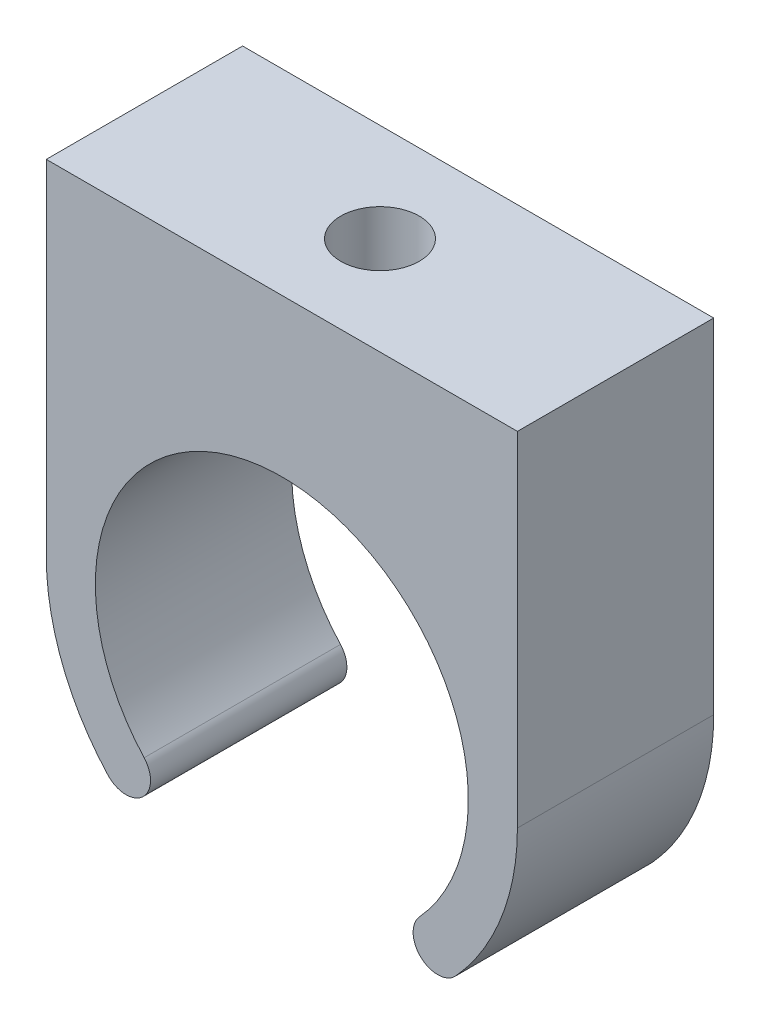
SolidWorks part; units mm, degrees
ref_plane "Front Plane" through (0, 0, 0) normal (0, 0, 1) x (1, 0, 0)
ref_plane "Top Plane" through (0, 0, 0) normal (0, 1, 0) x (1, 0, 0)
ref_plane "Right Plane" through (0, 0, 0) normal (1, 0, 0) x (0, 0, -1)
sketch "Sketch3" plane through (0, 0, 0) normal (0, 0, 1) x (1, 0, 0)
  line L2 (-12, -4.5) -> (-12, 13)
  line L3 (-12, 13) -> (12, 13)
  line L4 (12, -4.5) -> (12, 13)
  line L5 (-10.1145, -10.9573) -> (3.8592, 4.1808) construction
  line L6 (-5.6289, 6.0979) -> (10.1145, -10.9573) construction
  arc A1 (7.0143, -10.907) -> (-7.0143, -10.907) centre (0, -4.5) ccw
  arc A2 (8.8602, -12.593) -> (12, -4.5) centre (0, -4.5) ccw
  arc A3 (-8.8602, -12.593) -> (-7.0143, -10.907) centre (-7.9373, -11.75) ccw
  arc A4 (7.0143, -10.907) -> (8.8602, -12.593) centre (7.9373, -11.75) ccw
  arc A5 (-12, -4.5) -> (-8.8602, -12.593) centre (0, -4.5) ccw
  point P0 (0, 0)
  dimension "D4" = 19
  dimension "D2" = 12
  dimension "D1" = 24
extrude "Boss-Extrude2" add sketch "Sketch3" along normal mid plane 10
sketch "Sketch5" plane through (0, 13, 0) normal (0, 1, 0) x (1, 0, 0)
  line L0 (-12, 5) -> (12, -5) construction
  circle A0 centre (0, 0) radius 2
  dimension "D1" = 4
extrude "Cut-Extrude1" cut sketch "Sketch5" against normal blind 9
sketch "Sketch7" plane through (0, 0, -5) normal (0, 0, -1) x (-1, 0, 0)
  line L0 (0, -3.3243) -> (0, 13) construction
  line L1 (-12, 13) -> (12, 13) construction
  line L6 (10, 11.1905) -> (10, 1.1905)
  line L7 (10, 11.1905) -> (5, 11.1905)
  line L8 (5, 11.1905) -> (5, 6.1905)
  line L9 (-10, 11.1905) -> (-10, 1.1905)
  line L10 (-5, 11.1905) -> (-5, 6.1905)
  line L11 (-10, 11.1905) -> (-5, 11.1905)
  arc A0 (5, 6.1905) -> (10, 1.1905) centre (5, 1.1905) cw
  arc A1 (-5, 6.1905) -> (-10, 1.1905) centre (-5, 1.1905) ccw
  dimension "D4" = 10
  dimension "D5" = 5
  dimension "D6" = 5
extrude "Cut-Extrude2" cut sketch "Sketch7" against normal blind 8
